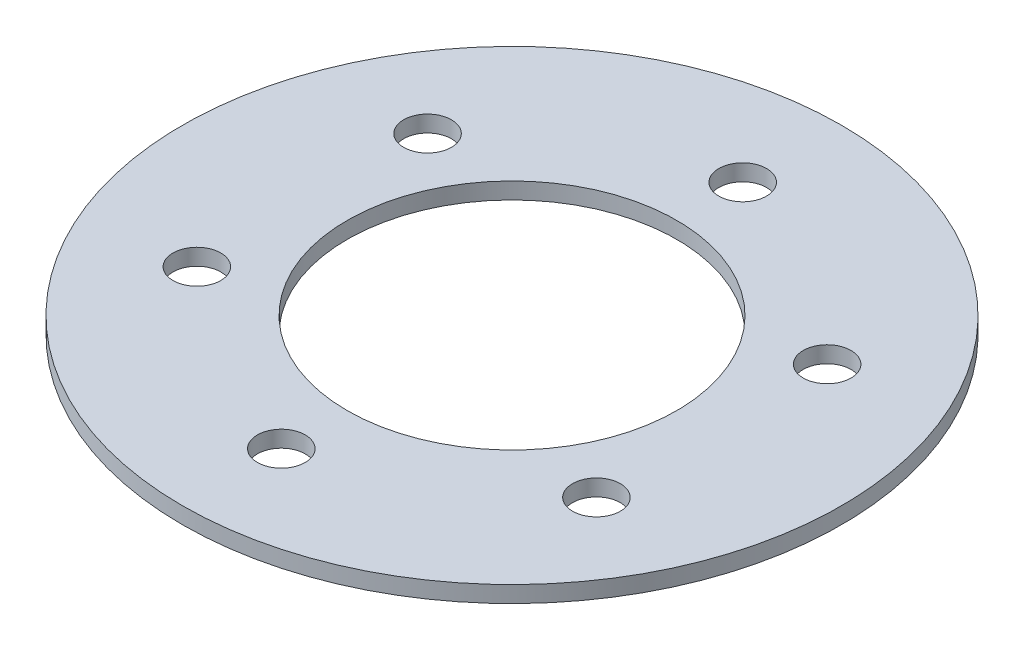
SolidWorks part; units mm, degrees
ref_plane "前视基准面" through (0, 0, 0) normal (0, 0, 1) x (1, 0, 0)
ref_plane "上视基准面" through (0, 0, 0) normal (0, 1, 0) x (1, 0, 0)
ref_plane "右视基准面" through (0, 0, 0) normal (1, 0, 0) x (0, 0, -1)
sketch "草图1" plane through (0, 0, 0) normal (0, 1, 0) x (1, 0, 0)
  line L1 (-12.1244, -7) -> (0, -14) construction
  line L2 (0, -14) -> (12.1244, -7) construction
  line L3 (12.1244, -7) -> (12.1244, 7) construction
  line L4 (12.1244, 7) -> (0, 14) construction
  line L5 (0, 14) -> (-12.1244, 7) construction
  line L6 (-12.1244, 7) -> (-12.1244, -7) construction
  circle A0 centre (0, 0) radius 20
  circle A1 centre (0, 0) radius 14 construction
  circle A2 centre (0, 0) radius 12.1244 construction
  circle A3 centre (0, 14) radius 1.45
  circle A4 centre (-12.1244, 7) radius 1.45
  circle A5 centre (-12.1244, -7) radius 1.45
  circle A6 centre (0, -14) radius 1.45
  circle A7 centre (12.1244, -7) radius 1.45
  circle A8 centre (12.1244, 7) radius 1.45
  circle A9 centre (0, 0) radius 10
  dimension "D1" = 40
  dimension "D2" = 28
  dimension "D3" = 2.9
  dimension "D4" = 20
extrude "凸台-拉伸1" add sketch "草图1" along normal blind 1
